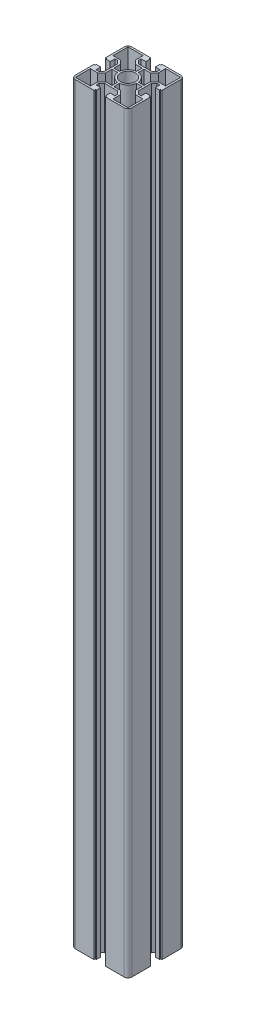
SolidWorks part; units mm, degrees
ref_plane "前视基准面" through (0, 0, 0) normal (0, 0, 1) x (1, 0, 0)
ref_plane "上视基准面" through (0, 0, 0) normal (0, 1, 0) x (1, 0, 0)
ref_plane "右视基准面" through (0, 0, 0) normal (1, 0, 0) x (0, 0, -1)
sketch "草图1" plane through (0, 0, 0) normal (0, 1, 0) x (1, 0, 0)
  line L0 (0, 32.6515) -> (0, -47.5) construction
  line L2 (-54.5455, 0) -> (57.7273, 0) construction
  line L82 (-16, 1) -> (-9.9499, 1)
  line L83 (-30, 6) -> (-28.5, 6)
  line L88 (-16, 1) -> (-16, 7.8284)
  line L89 (-16, 7.8284) -> (-20.1716, 12)
  line L90 (-20.1716, 12) -> (-28, 12)
  line L91 (-28, 12) -> (-28, 28)
  line L92 (-28, 28) -> (-12, 28)
  line L93 (-12, 28) -> (-12, 20.1716)
  line L94 (-12, 20.1716) -> (-7.8284, 16)
  line L95 (-7.8284, 16) -> (-1, 16)
  line L96 (-1, 16) -> (-1, 9.9499)
  line L97 (1, 9.9499) -> (1, 16)
  line L98 (1, 16) -> (7.8284, 16)
  line L99 (7.8284, 16) -> (12, 20.1716)
  line L100 (12, 20.1716) -> (12, 28)
  line L101 (12, 28) -> (28, 28)
  line L102 (28, 28) -> (28, 12)
  line L103 (28, 12) -> (20.1716, 12)
  line L104 (20.1716, 12) -> (16, 7.8284)
  line L105 (16, 7.8284) -> (16, 1)
  line L106 (16, 1) -> (9.9499, 1)
  line L107 (9.9499, -1) -> (16, -1)
  line L108 (16, -1) -> (16, -7.8284)
  line L109 (16, -7.8284) -> (20.1716, -12)
  line L110 (20.1716, -12) -> (28, -12)
  line L111 (28, -12) -> (28, -28)
  line L112 (28, -28) -> (12, -28)
  line L113 (12, -28) -> (12, -20.1716)
  line L114 (12, -20.1716) -> (7.8284, -16)
  line L115 (7.8284, -16) -> (1, -16)
  line L116 (1, -16) -> (1, -9.9499)
  line L117 (-1, -9.9499) -> (-1, -16)
  line L118 (-1, -16) -> (-7.8284, -16)
  line L119 (-7.8284, -16) -> (-12, -20.1716)
  line L120 (-12, -20.1716) -> (-12, -28)
  line L121 (-12, -28) -> (-28, -28)
  line L122 (-28, -28) -> (-28, -12)
  line L123 (-28, -12) -> (-20.1716, -12)
  line L124 (-20.1716, -12) -> (-16, -7.8284)
  line L125 (-16, -7.8284) -> (-16, -1)
  line L126 (-28.5, 6) -> (-28.5, 5)
  line L127 (-28.5, 5) -> (-24, 5)
  line L128 (-24, 5) -> (-24, 10)
  line L129 (-24, 10) -> (-21, 10)
  line L130 (-21, 10) -> (-18, 7)
  line L131 (-18, 7) -> (-18, -7)
  line L132 (-18, -7) -> (-21, -10)
  line L133 (-21, -10) -> (-24, -10)
  line L134 (-24, -10) -> (-24, -5)
  line L135 (-24, -5) -> (-28.5, -5)
  line L136 (-28.5, -5) -> (-28.5, -6)
  line L137 (-28.5, -6) -> (-30, -6)
  line L138 (-30, -6) -> (-30, -26)
  line L139 (-26, -30) -> (-6, -30)
  line L140 (-6, -30) -> (-6, -28.5)
  line L141 (-6, -28.5) -> (-5, -28.5)
  line L142 (-5, -28.5) -> (-5, -24)
  line L143 (-5, -24) -> (-10, -24)
  line L144 (-10, -24) -> (-10, -21)
  line L145 (-10, -21) -> (-7, -18)
  line L146 (-7, -18) -> (7, -18)
  line L147 (7, -18) -> (10, -21)
  line L148 (10, -21) -> (10, -24)
  line L149 (10, -24) -> (5, -24)
  line L150 (5, -24) -> (5, -28.5)
  line L151 (5, -28.5) -> (6, -28.5)
  line L152 (6, -28.5) -> (6, -30)
  line L153 (6, -30) -> (26, -30)
  line L154 (30, -26) -> (30, -6)
  line L155 (30, -6) -> (28.5, -6)
  line L156 (28.5, -6) -> (28.5, -5)
  line L157 (28.5, -5) -> (24, -5)
  line L158 (24, -5) -> (24, -10)
  line L159 (24, -10) -> (21, -10)
  line L160 (21, -10) -> (18, -7)
  line L161 (18, -7) -> (18, 7)
  line L162 (18, 7) -> (21, 10)
  line L163 (21, 10) -> (24, 10)
  line L164 (24, 10) -> (24, 5)
  line L165 (24, 5) -> (28.5, 5)
  line L166 (28.5, 5) -> (28.5, 6)
  line L167 (28.5, 6) -> (30, 6)
  line L168 (30, 6) -> (30, 26)
  line L169 (26, 30) -> (6, 30)
  line L170 (6, 30) -> (6, 28.5)
  line L171 (6, 28.5) -> (5, 28.5)
  line L172 (5, 28.5) -> (5, 24)
  line L173 (5, 24) -> (10, 24)
  line L174 (10, 24) -> (10, 21)
  line L175 (10, 21) -> (7, 18)
  line L176 (7, 18) -> (-7, 18)
  line L177 (-7, 18) -> (-10, 21)
  line L178 (-10, 21) -> (-10, 24)
  line L179 (-10, 24) -> (-5, 24)
  line L180 (-5, 24) -> (-5, 28.5)
  line L181 (-5, 28.5) -> (-6, 28.5)
  line L182 (-6, 28.5) -> (-6, 30)
  line L183 (-6, 30) -> (-26, 30)
  line L184 (-30, 26) -> (-30, 6)
  line L185 (-16, -1) -> (-9.9499, -1)
  arc A41 (-9.9499, -1) -> (-1, -9.9499) centre (0, 0) ccw
  circle A42 centre (0, 0) radius 8
  arc A43 (-26, -30) -> (-30, -26) centre (-26, -26) cw
  arc A44 (26, 30) -> (30, 26) centre (26, 26) cw
  arc A45 (-26, 30) -> (-30, 26) centre (-26, 26) ccw
  arc A46 (26, -30) -> (30, -26) centre (26, -26) ccw
  arc A47 (9.9499, 1) -> (1, 9.9499) centre (0, 0) ccw
  arc A48 (-1, 9.9499) -> (-9.9499, 1) centre (0, 0) ccw
  arc A49 (1, -9.9499) -> (9.9499, -1) centre (0, 0) ccw
extrude "凸台-拉伸1" add sketch "草图1" along normal blind 800
ref_plane "基准面1" through (0, 400, 0) normal (0, 1, 0) x (1, 0, 0)
